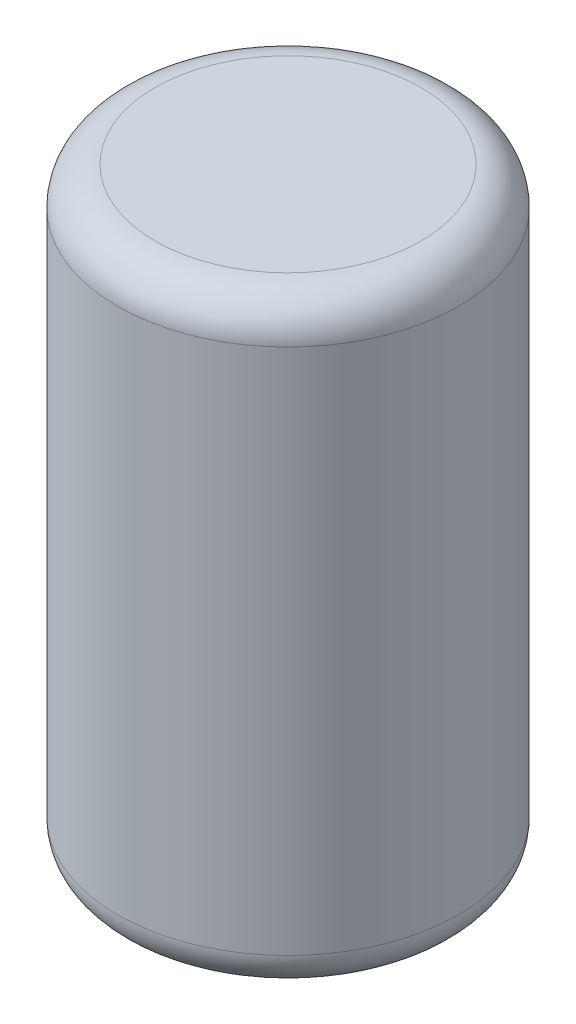
SolidWorks part; units mm, degrees
ref_plane "Front Plane" through (0, 0, 0) normal (0, 0, 1) x (1, 0, 0)
ref_plane "Top Plane" through (0, 0, 0) normal (0, 1, 0) x (1, 0, 0)
ref_plane "Right Plane" through (0, 0, 0) normal (1, 0, 0) x (0, 0, -1)
sketch "Sketch1" plane through (0, 0, 0) normal (0, 1, 0) x (1, 0, 0)
  circle A0 centre (0, 0) radius 3.4
  dimension "D1" = 6.8
extrude "Boss-Extrude1" add sketch "Sketch1" along normal blind 12
fillet "Fillet1" radius 0.75 2 edges at (0, 0, 3.4) (0, 12, 3.4)
